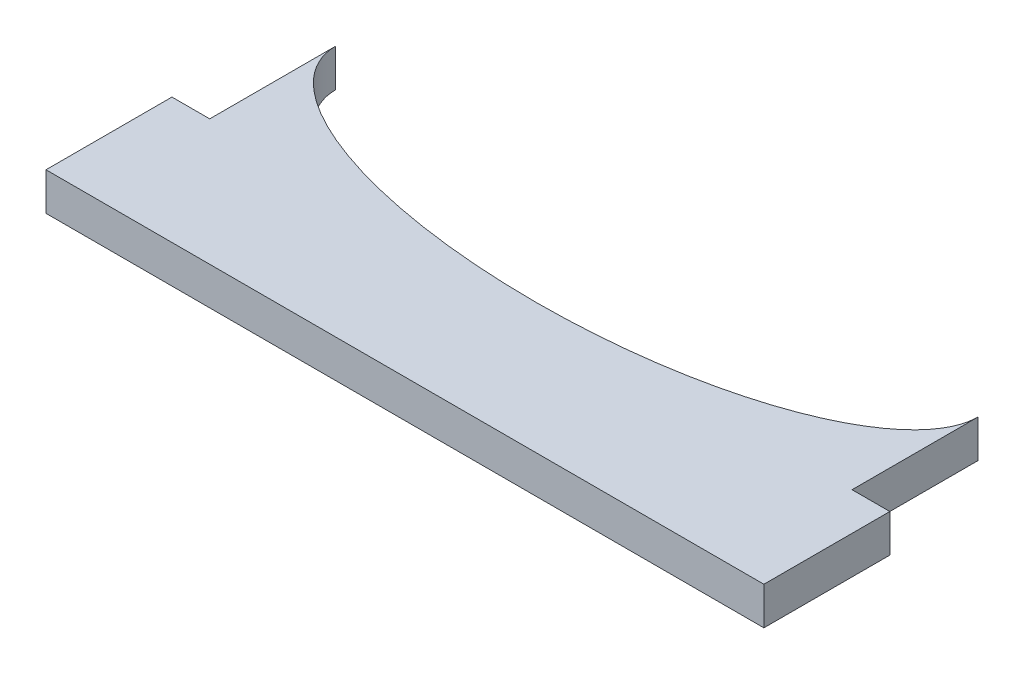
SolidWorks part; units mm, degrees
ref_plane "Front Plane" through (0, 0, 0) normal (0, 0, 1) x (1, 0, 0)
ref_plane "Top Plane" through (0, 0, 0) normal (0, 1, 0) x (1, 0, 0)
ref_plane "Right Plane" through (0, 0, 0) normal (1, 0, 0) x (0, 0, -1)
sketch "Sketch2" plane through (0, 0, 0) normal (0, 1, 0) x (1, 0, 0)
  line L0 (25.5, 20) -> (25.5, 0)
  line L1 (0, 0) -> (51, 0)
  line L2 (0, 10) -> (0, 20)
  line L3 (0, 20) -> (51, 20)
  line L4 (51, 10) -> (51, 20)
  line L5 (0, 10) -> (-3, 10)
  line L7 (0, 0) -> (-3, 0)
  line L8 (-3, 10) -> (-3, 0)
  line L9 (51, 0) -> (54, 0)
  line L10 (54, 10) -> (54, 0)
  line L11 (51, 10) -> (54, 10)
  ellipse E0 centre (25.5, 20) end of major axis (51, 20) minor radius 9.6635
  point P13 (-52.891, 0)
  dimension "D1" = 51
  dimension "D2" = 20
  dimension "D3" = 3
  dimension "D4" = 10
  dimension "D5" = 51
extrude "Boss-Extrude1" add sketch "Sketch2" along normal blind 3 contours E0 L2 L5 L8 L7 L1 L0 | E0 L0 L1 L9 L10 L11 L4
